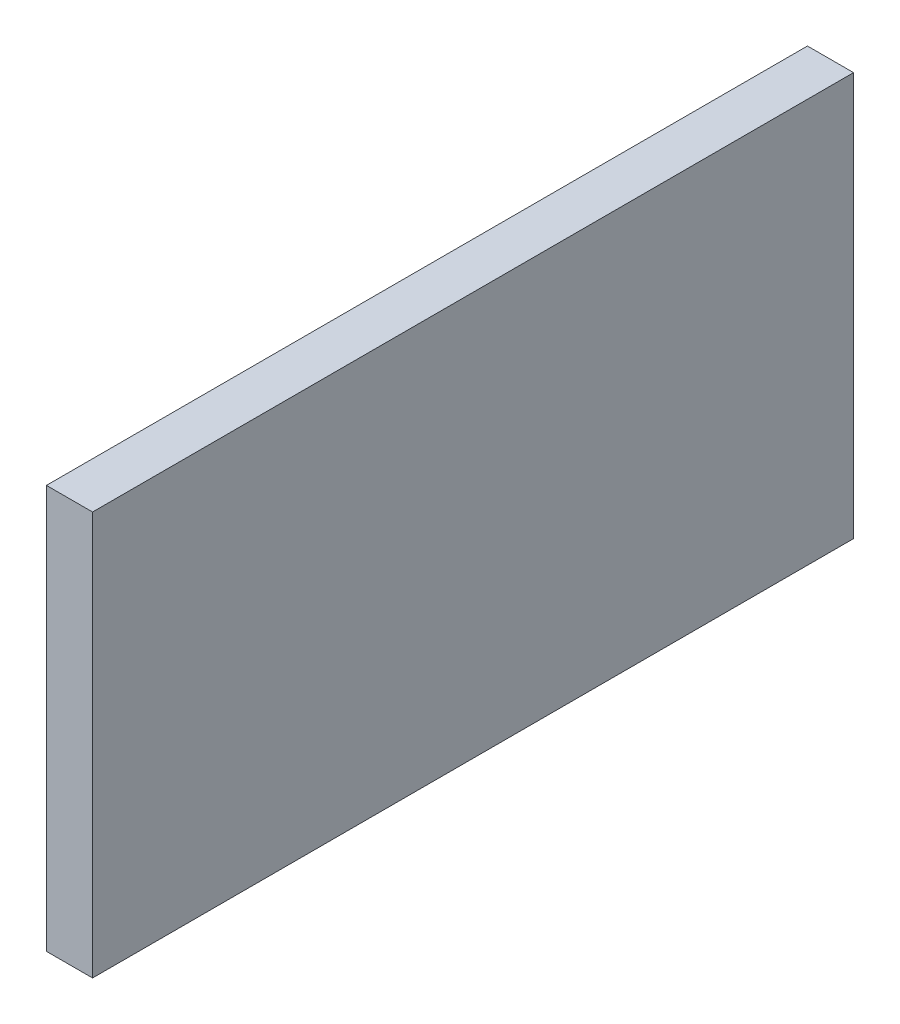
SolidWorks part; units mm, degrees
ref_plane "Front Plane" through (0, 0, 0) normal (0, 0, 1) x (1, 0, 0)
ref_plane "Top Plane" through (0, 0, 0) normal (0, 1, 0) x (1, 0, 0)
ref_plane "Right Plane" through (0, 0, 0) normal (1, 0, 0) x (0, 0, -1)
sketch "Sketch1" plane through (0, 0, 0) normal (0, 0, 1) x (1, 0, 0)
  line L1 (0, 0) -> (4, 0)
  line L2 (0, 0) -> (0, 35)
  line L3 (0, 35) -> (4, 35)
  line L4 (4, 0) -> (4, 35)
  dimension "D1" = 4
  dimension "D2" = 35
extrude "Profile" add sketch "Sketch1" along normal blind 66
equation "\"Profile_Depth\"= 66mm"
equation "\"D1@Profile\" = \"Profile_Depth\""
equation "\"Profile_Sketch_1\"= 4mm"
equation "\"D1@Sketch1\" = \"Profile_Sketch_1\""
equation "\"Profile_Sketch_2\"= 35mm"
equation "\"D2@Sketch1\" = \"Profile_Sketch_2\""
equation "\"EnvelopeWidth\"= 4mm"
equation "\"EnvelopeHeight\"= 35mm"
